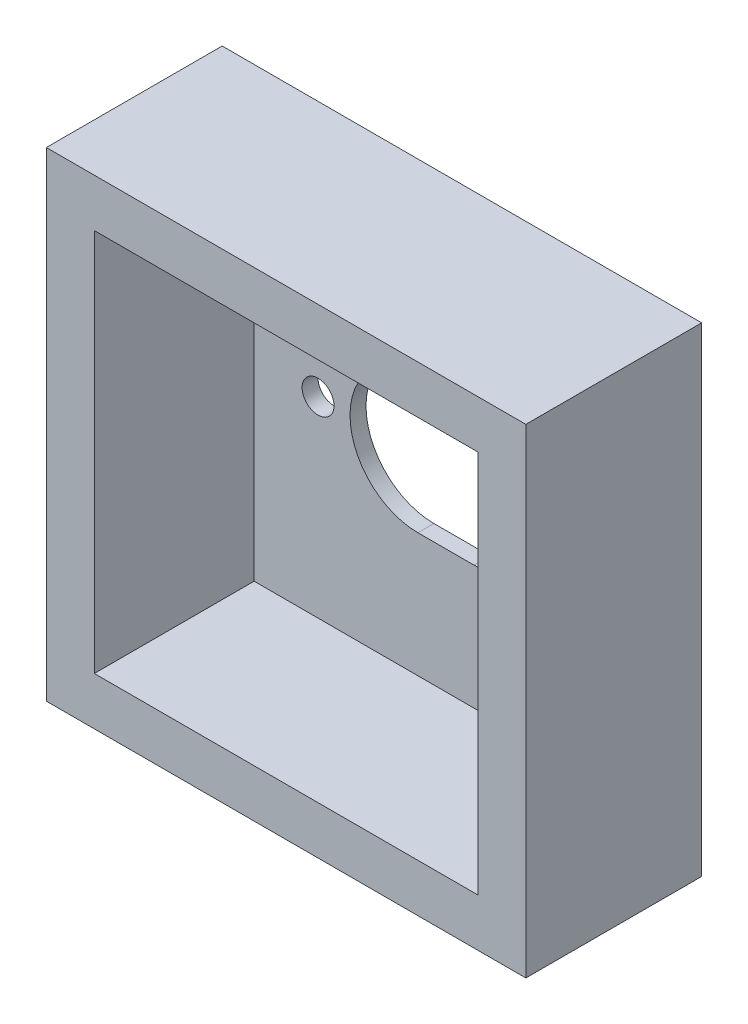
SolidWorks part; units mm, degrees
ref_plane "Plan de face" through (0, 0, 0) normal (0, 0, 1) x (1, 0, 0)
ref_plane "Plan de dessus" through (0, 0, 0) normal (0, 1, 0) x (1, 0, 0)
ref_plane "Plan de droite" through (0, 0, 0) normal (1, 0, 0) x (0, 0, -1)
sketch "Croquis1" plane through (0, 0, 0.6) normal (0, 0, 1) x (1, 0, 0)
  line L0 (-1.75, 4.25) -> (1.75, 4.25)
  line L1 (-15, 15) -> (15, 15)
  line L2 (-15, 15) -> (-15, -15)
  line L3 (-15, -15) -> (15, -15)
  line L4 (15, 15) -> (15, -15)
  line L5 (1.75, -4.25) -> (-1.75, -4.25)
  arc A0 (-1.75, 4.25) -> (-1.75, -4.25) centre (-1.75, 0) ccw
  arc A1 (1.75, -4.25) -> (1.75, 4.25) centre (1.75, 0) ccw
  circle A2 centre (-8, 0) radius 1
  circle A3 centre (8, 0) radius 1
extrude "Saliente-Extruir2" add sketch "Croquis1" against normal blind 1
sketch "Croquis2" plane through (0, 0, 0.6) normal (0, 0, 1) x (1, 0, 0)
  line L1 (-15, 15) -> (15, 15)
  line L2 (-15, 15) -> (-15, -15)
  line L3 (-15, -15) -> (15, -15)
  line L4 (15, 15) -> (15, -15)
  line L5 (-12, 12) -> (12, 12)
  line L6 (-12, 12) -> (-12, -12)
  line L7 (-12, -12) -> (12, -12)
  line L8 (12, 12) -> (12, -12)
  dimension "D1" = 3
  dimension "D2" = 3
  dimension "D3" = 3
  dimension "D4" = 3
extrude "Saliente-Extruir3" add sketch "Croquis2" along normal blind 10
